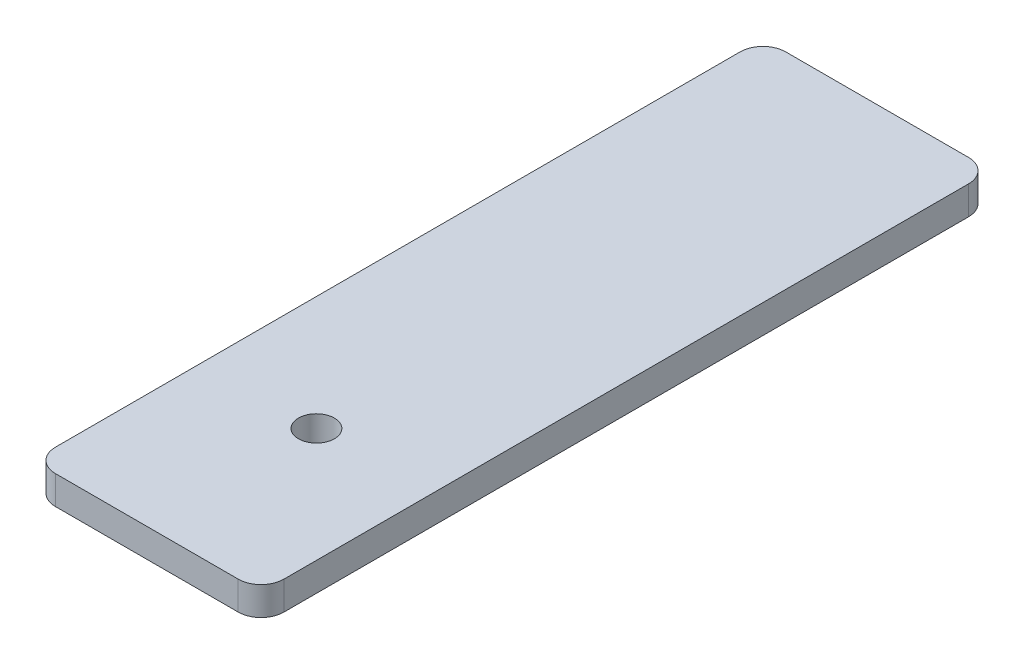
SolidWorks part; units mm, degrees
material "Acrylic (Medium-high impact)"
ref_plane "Front Plane" through (0, 0, 0) normal (0, 0, 1) x (1, 0, 0)
ref_plane "Top Plane" through (0, 0, 0) normal (0, 1, 0) x (1, 0, 0)
ref_plane "Right Plane" through (0, 0, 0) normal (1, 0, 0) x (0, 0, -1)
ref_plane "Plane1" through (0, 0, 0) normal (0, 1, 0) x (1, 0, 0)
sketch "Sketch1" plane through (0, 0, 0) normal (0, 1, 0) x (1, 0, 0)
  line L1 (-26.2811, -24.9588) -> (-0.8811, -24.9588)
  line L2 (-26.2811, -24.9588) -> (-26.2811, 56.2162)
  line L3 (-26.2811, 56.2162) -> (-0.8811, 56.2162)
  line L4 (-0.8811, -24.9588) -> (-0.8811, 56.2162)
  dimension "D1" = 81.175
  dimension "D2" = 25.4
extrude "Boss-Extrude1" add sketch "Sketch1" along normal blind 3.175
sketch "Sketch2" plane through (0, 3.175, 0) normal (0, 1, 0) x (1, 0, 0)
  line L0 (-26.2811, -24.9588) -> (-0.8811, -24.9588) construction
  line L1 (-26.2811, 56.2162) -> (-26.2811, -24.9588) construction
  circle A0 centre (-13.5811, -6.1088) radius 2
  dimension "D2" = 4
  dimension "D1" = 18.85
  dimension "D3" = 12.7
extrude "Cut-Extrude1" cut sketch "Sketch2" against normal through all
fillet "Fillet1" radius 2.54 4 edges at (-26.2811, 1.5875, -56.2162) (-0.8811, 1.5875, -56.2162) (-0.8811, 1.5875, 24.9588) (-26.2811, 1.5875, 24.9588)
